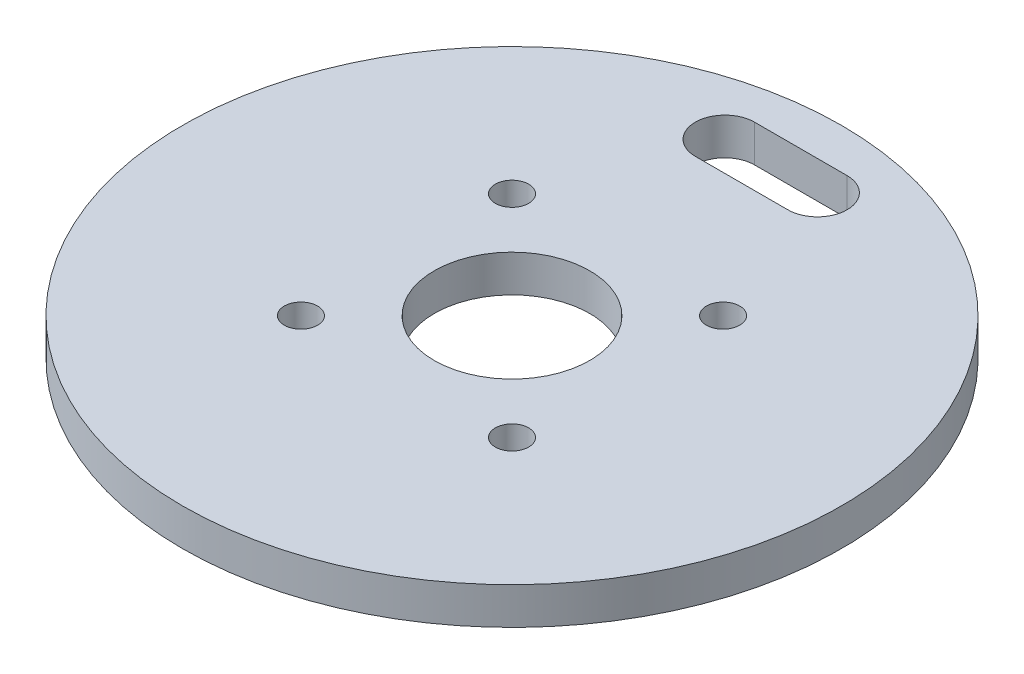
SolidWorks part; units mm, degrees
ref_plane "Front Plane" through (0, 0, 0) normal (0, 0, 1) x (1, 0, 0)
ref_plane "Top Plane" through (0, 0, 0) normal (0, 1, 0) x (1, 0, 0)
ref_plane "Right Plane" through (0, 0, 0) normal (1, 0, 0) x (0, 0, -1)
sketch "Sketch1" plane through (0, 0, 0) normal (0, 1, 0) x (1, 0, 0)
  circle A0 centre (0, 0) radius 44.5
  circle A1 centre (0, 0) radius 10.5
  dimension "D1" = 89
  dimension "D2" = 21
extrude "Body" add sketch "Sketch1" along normal blind 5
sketch "Sketch5" plane through (0, 5, 0) normal (0, 1, 0) x (1, 0, 0)
  line L0 (-6.25, 35) -> (6.25, 35) construction
  line L1 (-6.25, 39) -> (6.25, 39)
  line L2 (-6.25, 31) -> (6.25, 31)
  arc A0 (-6.25, 39) -> (-6.25, 31) centre (-6.25, 35) ccw
  arc A1 (6.25, 31) -> (6.25, 39) centre (6.25, 35) ccw
  point P2 (0, 35)
  dimension "D3" = 35
  dimension "D1" = 8
  dimension "D2" = 12.5
extrude "Wire_Hole" cut sketch "Sketch5" against normal through all
hole_wizard "M4 Clearance Hole1" positions "Sketch6" profile "Sketch7" hole size "M4" standard "ANSI Metric" end condition through all
sketch "Sketch6" plane through (0, 5, 0) normal (0, 1, 0) x (1, 0, 0)
  line L1 (14.25, -14.25) -> (-14.25, -14.25) construction
  line L2 (14.25, -14.25) -> (14.25, 14.25) construction
  line L3 (14.25, 14.25) -> (-14.25, 14.25) construction
  line L4 (-14.25, -14.25) -> (-14.25, 14.25) construction
  line L5 (14.25, -14.25) -> (-14.25, 14.25) construction
  line L6 (14.25, 14.25) -> (-14.25, -14.25) construction
  point P1 (-14.25, 14.25)
  point P16 (14.25, -14.25)
  point P17 (14.25, 14.25)
  point P18 (-14.25, -14.25)
  dimension "D1" = 28.5
  dimension "D2" = 28.5
sketch "Sketch7" plane through (-14.25, 5, -14.25) normal (1, 0, 0) x (0, 0, 1)
  line L0 (0, 0) -> (0, 5)
  line L1 (0, 5) -> (2.25, 5)
  line L2 (2.25, 5) -> (2.25, 0)
  line L5 (2.25, 0) -> (0, 0)
  line L11 (0, -6.35) -> (0, 107.95) construction
  dimension "Thru Hole Dia." = 4.5
  dimension "Thru Hole Depth" = 5
